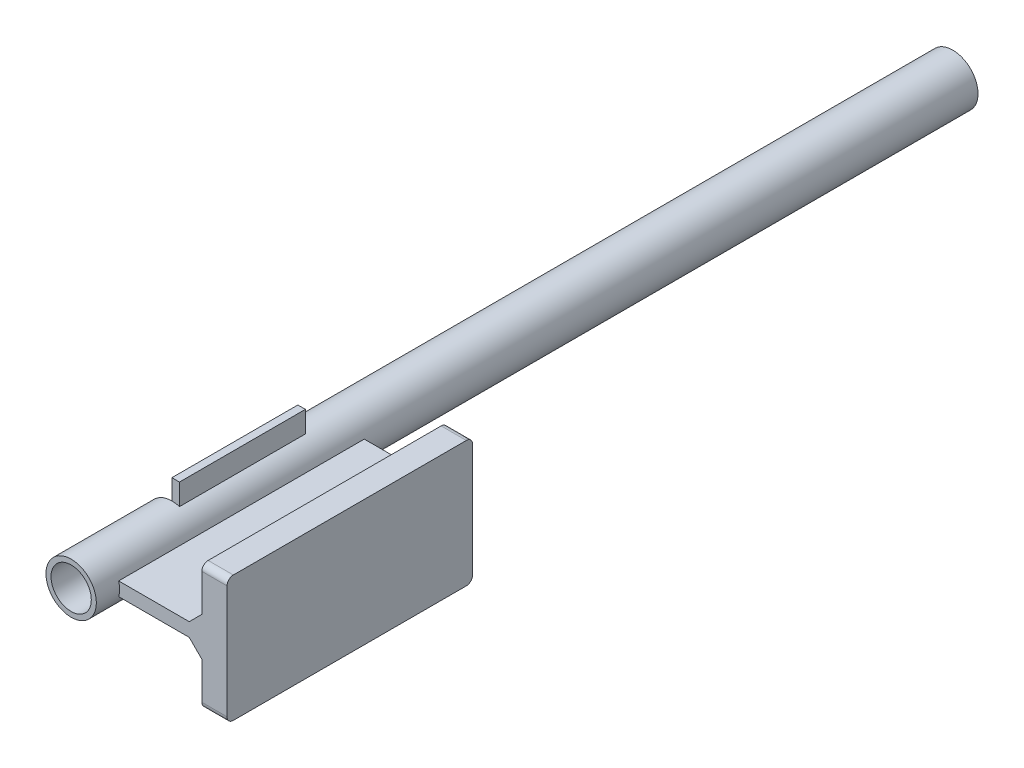
SolidWorks part; units mm, degrees
material "Plain Carbon Steel"
ref_plane "Front" through (0, 0, 0) normal (0, 0, 1) x (1, 0, 0)
ref_plane "Top" through (0, 0, 0) normal (0, 1, 0) x (1, 0, 0)
ref_plane "Right" through (0, 0, 0) normal (1, 0, 0) x (0, 0, -1)
sketch "Sketch1" plane through (0, 0, 0) normal (0, 0, 1) x (1, 0, 0)
  circle A0 centre (0, 0) radius 20
  circle A1 centre (0, 0) radius 16
  dimension "D1" = 32
  dimension "D2" = 4
extrude "Boss-Extrude1" add sketch "Sketch1" along normal mid plane 700
sketch "Sketch2" plane through (0, 0, 0) normal (0, 1, 0) x (1, 0, 0)
  line L0 (-46.7025, -220) -> (-146.9031, -220) construction
  line L1 (-46.7025, -270) -> (0, -270)
  line L2 (-46.7025, -270) -> (-46.7025, -170)
  line L3 (-46.7025, -170) -> (0, -170)
  line L4 (0, -270) -> (0, -170)
  line L5 (-50, 0) -> (50, 0) construction
  dimension "D1" = 100
  dimension "D2" = 220
extrude "Cut-Extrude1" cut sketch "Sketch2" against normal mid plane 200
sketch "Sketch3" plane through (0, 0, 0) normal (1, 0, 0) x (0, 0, -1)
  line L1 (-331.5262, -5.4087) -> (-136.5309, -5.4087)
  line L2 (-331.5262, -5.4087) -> (-331.5262, 5.4087)
  line L3 (-331.5262, 5.4087) -> (-136.5309, 5.4087)
  line L4 (-136.5309, -5.4087) -> (-136.5309, 5.4087)
  point P5 (-136.5309, 0)
extrude "Boss-Extrude2" add sketch "Sketch3" along normal blind 105.29
sketch "Sketch4" plane through (105.29, 0, 0) normal (1, 0, 0) x (0, 0, -1)
  line L0 (-331.5262, 5.4087) -> (-331.5262, -5.4087) construction
  line L1 (-136.5309, 50) -> (-331.5262, 50)
  line L2 (-136.5309, 50) -> (-136.5309, -50)
  line L3 (-136.5309, -50) -> (-331.5262, -50)
  line L4 (-331.5262, 50) -> (-331.5262, -50)
  line L5 (-136.5309, -5.4087) -> (-136.5309, 5.4087) construction
  line L6 (50, 0) -> (-50, 0) construction
  point P8 (-136.5309, 0)
  dimension "D1" = 100
extrude "Boss-Extrude3" add sketch "Sketch4" against normal blind 20
chamfer "Chamfer1" distance 10 angle 45 2 edges at (85.29, -5.4087, 234.0286) (85.29, 5.4087, 234.0286)
fillet "Fillet1" radius 5 4 edges at (95.29, -50, 331.5262) (95.29, -50, 136.5309) (95.29, 50, 136.5309) (95.29, 50, 331.5262)
sketch "Sketch5" plane through (0, 0, 0) normal (-1, 0, 0) x (0, 0, 1)
  line L0 (0, 0) -> (75.8441, 0) construction
  line L1 (270, 16) -> (170, 16)
  line L2 (270, 16) -> (270, 36)
  line L3 (270, 36) -> (170, 36)
  line L4 (170, 16) -> (170, 36)
  line L5 (170, 16) -> (270, 16) construction
  line L6 (220, -20) -> (220, -36) construction
  line L7 (220, 20) -> (220, 36) construction
  line L8 (170, 20) -> (270, 20) construction
  line L9 (170, -16) -> (170, -36)
  line L10 (270, -36) -> (170, -36)
  line L11 (270, -16) -> (270, -36)
  line L12 (270, -16) -> (170, -16)
  point P4 (195.6783, 20)
  dimension "D1" = 100
  dimension "D2" = 20
extrude "Boss-Extrude4" add sketch "Sketch5" against normal blind 6
